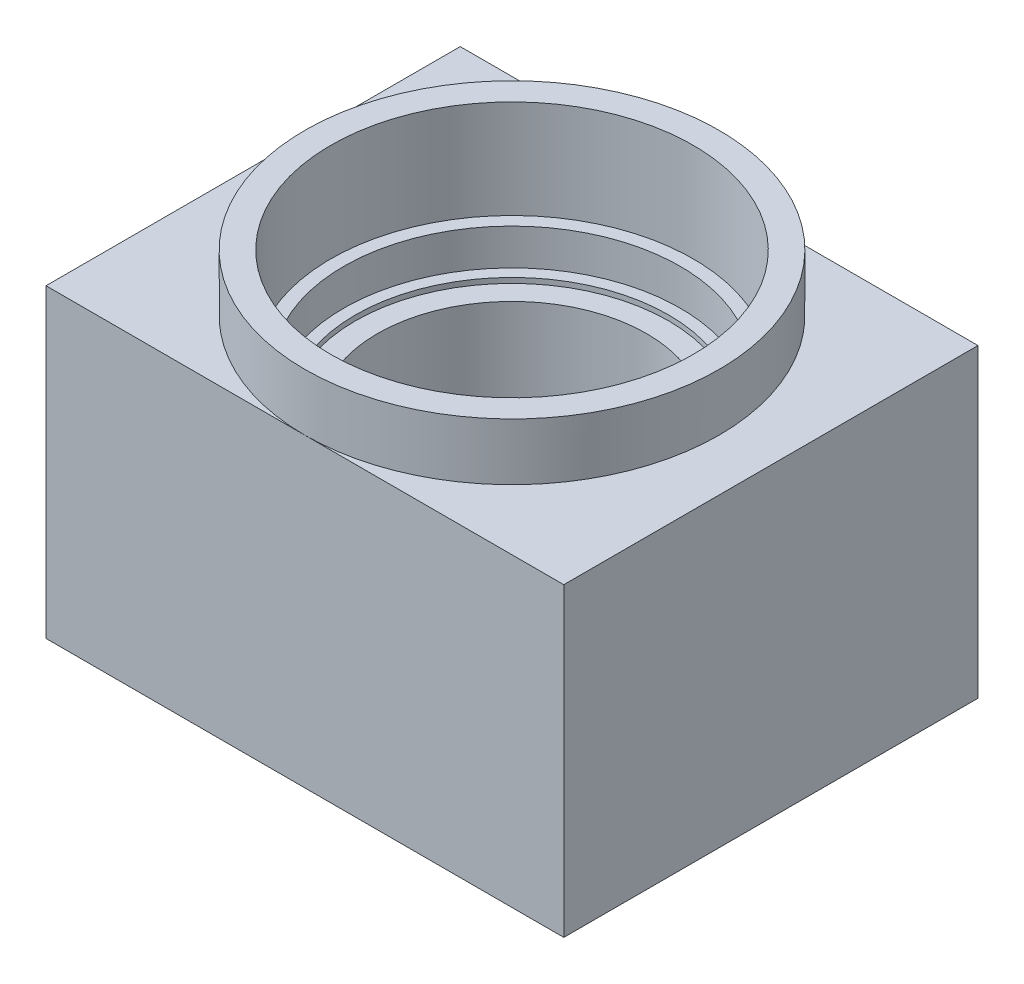
SolidWorks part; units mm, degrees
ref_plane "Front Plane" through (0, 0, 0) normal (0, 0, 1) x (1, 0, 0)
ref_plane "Top Plane" through (0, 0, 0) normal (0, 1, 0) x (1, 0, 0)
ref_plane "Right Plane" through (0, 0, 0) normal (1, 0, 0) x (0, 0, -1)
sketch "Sketch1" plane through (0, 0, 0) normal (0, 1, 0) x (1, 0, 0)
  line L1 (-50, 40) -> (50, 40)
  line L2 (-50, 40) -> (-50, -40)
  line L3 (-50, -40) -> (50, -40)
  line L4 (50, 40) -> (50, -40)
  line L5 (-50, 40) -> (50, -40) construction
  line L6 (-50, -40) -> (50, 40) construction
  circle A1 centre (0, 0) radius 26
  point P0 (0, 0)
  dimension "D3" = 52
  dimension "D1" = 80
  dimension "D2" = 100
extrude "Boss-Extrude1" add sketch "Sketch1" along normal blind 70
sketch "Sketch2" plane through (0, 70, 0) normal (0, 1, 0) x (1, 0, 0)
  circle A0 centre (0, 0) radius 32.5
  dimension "D1" = 65
extrude "Cut-Extrude1" cut sketch "Sketch2" against normal blind 27
sketch "Sketch4" plane through (0, 43, 0) normal (0, 1, 0) x (1, 0, 0)
  circle A0 centre (0, 0) radius 30.25
  circle M3 centre (0, 0) radius 32.5
  dimension "D1" = 60.5
extrude "Boss-Extrude2" add sketch "Sketch4" along normal blind 1 contours A0 M3
sketch "Sketch5" plane through (0, 70, 0) normal (0, 1, 0) x (1, 0, 0)
  circle A0 centre (0, 0) radius 35
  dimension "D1" = 70
extrude "Cut-Extrude2" cut sketch "Sketch5" against normal offset from surface (19 mm away) 7 up to face at (0, 44, 30.25)
sketch "Sketch6" plane through (0, 0, 0) normal (0, -1, 0) x (1, 0, 0)
  circle A0 centre (0, 0) radius 32.5
  dimension "D1" = 65
extrude "Cut-Extrude3" cut sketch "Sketch6" against normal blind 8
sketch "Sketch7" plane through (0, 8, 0) normal (0, -1, 0) x (1, 0, 0)
  circle A0 centre (0, 0) radius 30.25
  dimension "D1" = 60.5
extrude "Cut-Extrude4" cut sketch "Sketch7" against normal blind 1
sketch "Sketch8" plane through (0, 70, 0) normal (0, 1, 0) x (1, 0, 0)
  line L1 (-50, 40) -> (50, 40)
  line L2 (-50, 40) -> (-50, -40)
  line L3 (-50, -40) -> (50, -40)
  line L4 (50, 40) -> (50, -40)
  line L5 (-50, 40) -> (50, -40) construction
  line L6 (-50, -40) -> (50, 40) construction
  circle A0 centre (0, 0) radius 40
  line M3 (50, -40) -> (50, 40)
  line M4 (50, 40) -> (-50, 40)
  line M5 (-50, 40) -> (-50, -40)
  line M6 (-50, -40) -> (50, -40)
extrude "Cut-Extrude5" cut sketch "Sketch8" against normal blind 11 contours A0 L3 M3 M4 | A0 L1 M5 M6
